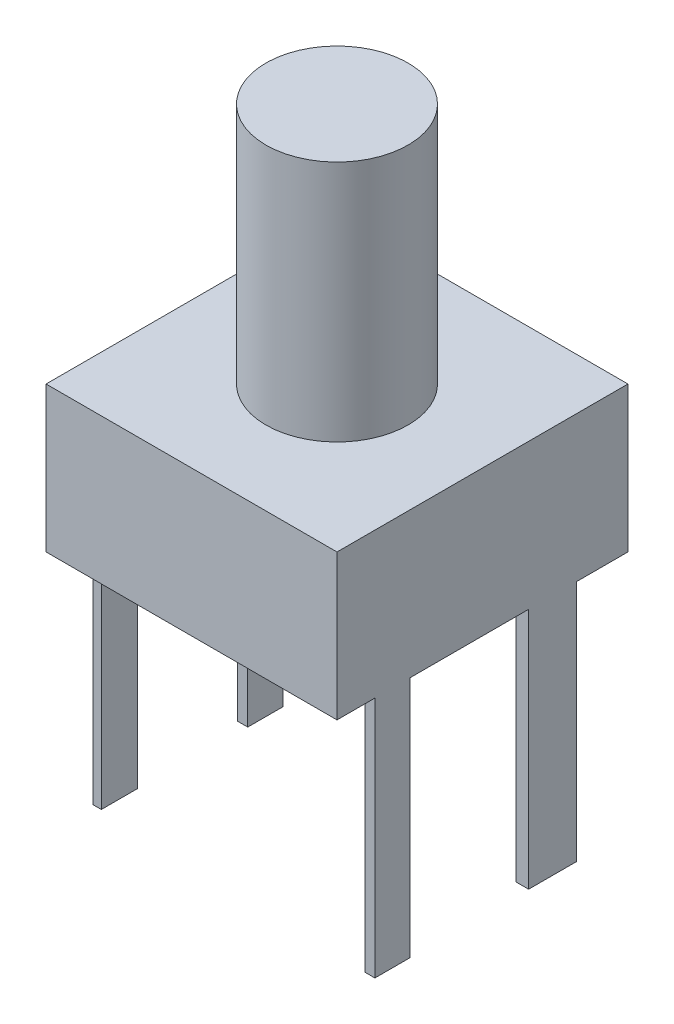
SolidWorks part; units mm, degrees
ref_plane "Front Plane" through (0, 0, 0) normal (0, 0, 1) x (1, 0, 0)
ref_plane "Top Plane" through (0, 0, 0) normal (0, 1, 0) x (1, 0, 0)
ref_plane "Right Plane" through (0, 0, 0) normal (1, 0, 0) x (0, 0, -1)
sketch "Sketch1" plane through (0, 0, 0) normal (0, 1, 0) x (1, 0, 0)
  line L1 (0, 0) -> (6, 0)
  line L2 (0, 0) -> (0, -6)
  line L3 (0, -6) -> (6, -6)
  line L4 (6, 0) -> (6, -6)
  dimension "D1" = 6
  dimension "D2" = 6
extrude "Boss-Extrude1" add sketch "Sketch1" along normal blind 3
sketch "Sketch2" plane through (0, 3, 0) normal (0, 1, 0) x (1, 0, 0)
  circle A0 centre (3, -3) radius 1.4661
extrude "Boss-Extrude2" add sketch "Sketch2" along normal blind 5
sketch "Sketch3" plane through (0, 0, 0) normal (0, -1, 0) x (-1, 0, 0)
  line L0 (0, 0) -> (0, -6) construction
  line L1 (0, -5.0296) -> (-0.1699, -5.0296)
  line L2 (0, -5.0296) -> (0, -4.2857)
  line L3 (0, -4.2857) -> (-0.1699, -4.2857)
  line L4 (-0.1699, -5.0296) -> (-0.1699, -4.2857)
  line L5 (-6, -6) -> (-6, 0) construction
  line L6 (0, -2.0485) -> (-0.2076, -2.0485)
  line L7 (0, -2.0485) -> (0, -1.3262)
  line L8 (0, -1.3262) -> (-0.2076, -1.3262)
  line L9 (-0.2076, -2.0485) -> (-0.2076, -1.3262)
  line L10 (-6, -5.2183) -> (-5.7924, -5.2183)
  line L11 (-6, -5.2183) -> (-6, -4.4959)
  line L12 (-6, -4.4959) -> (-5.7924, -4.4959)
  line L13 (-5.7924, -5.2183) -> (-5.7924, -4.4959)
  line L15 (-6, -2.0485) -> (-5.7385, -2.0485)
  line L16 (-6, -2.0485) -> (-6, -1.062)
  line L17 (-6, -1.062) -> (-5.7385, -1.062)
  line L18 (-5.7385, -2.0485) -> (-5.7385, -1.062)
extrude "Boss-Extrude3" add sketch "Sketch3" along normal blind 5
